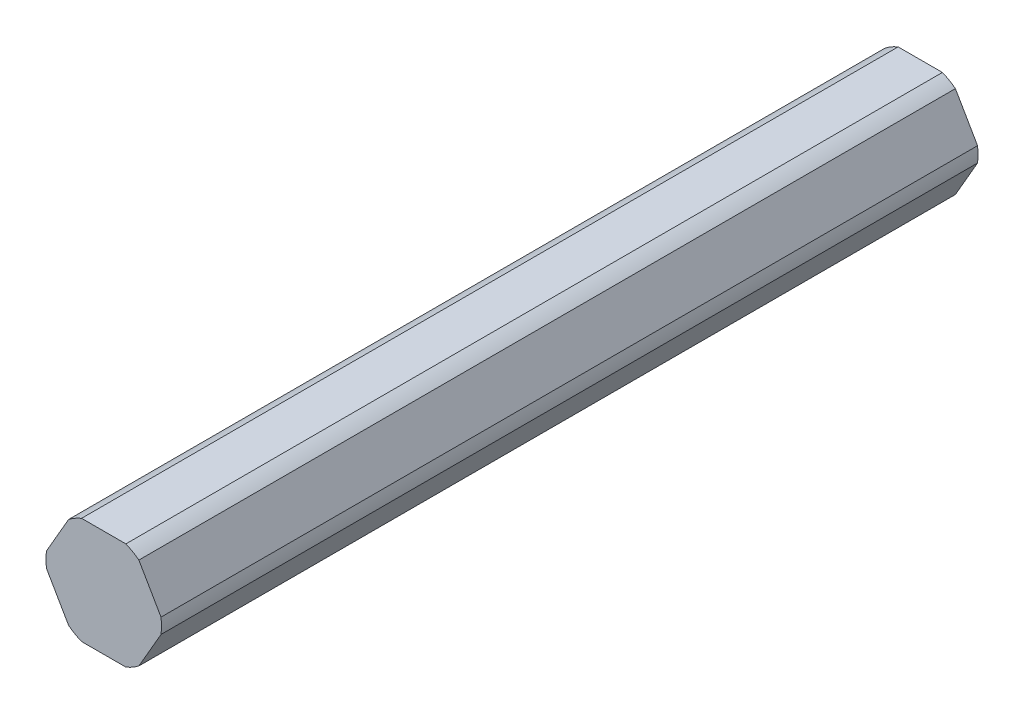
SolidWorks part; units mm, degrees
ref_plane "Front Plane" through (0, 0, 0) normal (0, 0, 1) x (1, 0, 0)
ref_plane "Top Plane" through (0, 0, 0) normal (0, 1, 0) x (1, 0, 0)
ref_plane "Right Plane" through (0, 0, 0) normal (1, 0, 0) x (0, 0, -1)
sketch "Sketch2" plane through (0, 0, 0) normal (0, 0, 1) x (1, 0, 0)
  line L1 (7.3323, 0) -> (3.6662, 6.35)
  line L2 (3.6662, 6.35) -> (-3.6662, 6.35)
  line L3 (-3.6662, 6.35) -> (-7.3323, 0)
  line L4 (-7.3323, 0) -> (-3.6662, -6.35)
  line L5 (-3.6662, -6.35) -> (3.6662, -6.35)
  line L6 (3.6662, -6.35) -> (7.3323, 0)
  circle A0 centre (0, 0) radius 6.35 construction
  dimension "D1" = 12.7
extrude "Boss-Extrude1" add sketch "Sketch2" along normal blind 7.9375
sketch "Sketch5" plane through (0, 0, 7.9375) normal (0, 0, 1) x (1, 0, 0)
  line L1 (7.3323, 0) -> (3.6662, 6.35)
  line L2 (3.6662, 6.35) -> (-3.6662, 6.35)
  line L3 (-3.6662, 6.35) -> (-7.3323, 0)
  line L4 (-7.3323, 0) -> (-3.6662, -6.35)
  line L5 (-3.6662, -6.35) -> (3.6662, -6.35)
  line L6 (3.6662, -6.35) -> (7.3323, 0)
  circle A0 centre (0, 0) radius 6.35 construction
extrude "Boss-Extrude4" add sketch "Sketch5" along normal blind 89.2175
sketch "Sketch6" plane through (0, 0, 97.155) normal (0, 0, 1) x (1, 0, 0)
  line L12 (3.6662, -6.35) -> (7.3323, 0)
  line L13 (7.3323, 0) -> (3.6662, 6.35)
  line L14 (3.6662, 6.35) -> (-3.6662, 6.35)
  line L15 (-3.6662, 6.35) -> (-7.3323, 0)
  line L16 (-7.3323, 0) -> (-3.6662, -6.35)
  line L17 (-3.6662, -6.35) -> (3.6662, -6.35)
  line L18 (3.6662, -6.35) -> (7.3323, 0)
  line L19 (7.3323, 0) -> (3.6662, 6.35)
  line L20 (3.6662, 6.35) -> (-3.6662, 6.35)
  line L21 (-3.6662, 6.35) -> (-7.3323, 0)
  line L22 (-7.3323, 0) -> (-3.6662, -6.35)
  line L23 (-3.6662, -6.35) -> (3.6662, -6.35)
  arc A0 (-6.8168, 0.893) -> (-6.8168, -0.893) centre (0, 0) ccw
  arc A1 (-2.635, 6.35) -> (-4.1818, 5.457) centre (0, 0) ccw
  arc A2 (4.1818, 5.457) -> (2.635, 6.35) centre (0, 0) ccw
  arc A3 (6.8168, -0.893) -> (6.8168, 0.893) centre (0, 0) ccw
  arc A4 (2.635, -6.35) -> (4.1818, -5.457) centre (0, 0) ccw
  arc A5 (-4.1818, -5.457) -> (-2.635, -6.35) centre (0, 0) ccw
  line M1 (3.6662, -6.35) -> (7.3323, 0)
  line M2 (7.3323, 0) -> (3.6662, 6.35)
  line M3 (3.6662, 6.35) -> (-3.6662, 6.35)
  line M4 (-3.6662, 6.35) -> (-7.3323, 0)
  line M5 (-7.3323, 0) -> (-3.6662, -6.35)
  line M6 (-3.6662, -6.35) -> (3.6662, -6.35)
  dimension "D1" = 0
extrude "Cut-Extrude2" cut sketch "Sketch6" against normal through all contours A1 L20 M4 | A2 L19 M3 | A3 L18 M2 | A4 L23 M1 | A5 M5 M6 | A0 L21 M5
